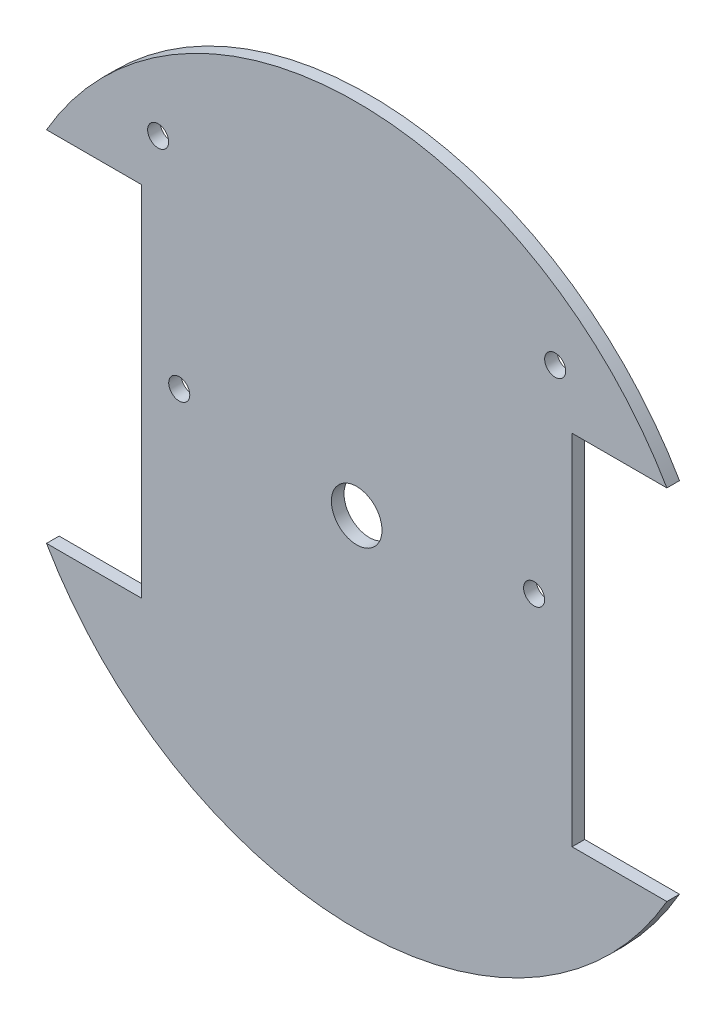
SolidWorks part; units mm, degrees
ref_plane "Plan de face" through (0, 0, 0) normal (0, 0, 1) x (1, 0, 0)
ref_plane "Plan de dessus" through (0, 0, 0) normal (0, 1, 0) x (1, 0, 0)
ref_plane "Plan de droite" through (0, 0, 0) normal (1, 0, 0) x (0, 0, -1)
sketch "Esquisse1" plane through (0, 0, 0) normal (0, 0, 1) x (1, 0, 0)
  circle A0 centre (-147.9597, 62.5489) radius 85
  dimension "D1" = 170
extrude "Boss.-Extru.1" add sketch "Esquisse1" along normal blind 3
sketch "Esquisse2" plane through (0, 0, 0) normal (0, 0, 1) x (1, 0, 0)
  line L0 (-147.9597, 147.5489) -> (-147.9597, -22.4511) construction
  line L1 (-231.5719, 105.0489) -> (-199.0719, 105.0489)
  line L2 (-231.5719, 105.0489) -> (-231.5719, 20.0489)
  line L3 (-231.5719, 20.0489) -> (-199.0719, 20.0489)
  line L4 (-199.0719, 105.0489) -> (-199.0719, 20.0489)
  line L5 (-62.9597, 62.5489) -> (-232.9597, 62.5489) construction
  line L6 (-231.5719, 62.5489) -> (-201.5719, 62.5489) construction
  line L7 (-64.3476, 20.0489) -> (-96.8476, 20.0489)
  line L8 (-64.3476, 105.0489) -> (-64.3476, 20.0489)
  line L9 (-64.3476, 105.0489) -> (-96.8476, 105.0489)
  line L10 (-96.8476, 105.0489) -> (-96.8476, 20.0489)
  circle A0 centre (-147.9597, 62.5489) radius 85 construction
  arc A1 (-221.5719, 105.0489) -> (-221.5719, 20.0489) centre (-147.9597, 62.5489) ccw
  arc A2 (-74.3476, 105.0489) -> (-74.3476, 20.0489) centre (-147.9597, 62.5489) ccw
  dimension "D1" = 85
  dimension "D2" = 32.5
extrude "Enlèv. mat.-Extru.6" cut sketch "Esquisse2" against normal blind 3 from surface at 3 contours L1 A1 L2 L3 L4 | L9 L10 L7 L8 starting at face at (-62.9597, 62.5489, 3)
delete or keep bodies "Corps-Supprimer/Garder 1" type delete bodies bodies 104 103
sketch "Esquisse53" plane through (0, 0, 0) normal (0, 0, -1) x (-1, 0, 0)
  line L0 (199.0719, 62.5489) -> (96.8476, 62.5489) construction
  line L1 (199.0719, 20.0489) -> (199.0719, 105.0489) construction
  line L2 (96.8476, 20.0489) -> (96.8476, 105.0489) construction
  line L3 (105.8476, 62.5489) -> (105.8476, 22.5155) construction
  line L4 (105.8476, 22.5155) -> (190.0719, 22.5155) construction
  line L5 (190.0719, 22.5155) -> (190.0719, 62.5489) construction
  circle A0 centre (190.0719, 67.5489) radius 2.5
  circle A1 centre (105.8476, 67.5489) radius 2.5
  dimension "D3" = 0
  dimension "D1" = 9
  dimension "D2" = 9
  dimension "D4" = 5
  dimension "D5" = 5
extrude "Enlèv. mat.-Extru.21" cut sketch "Esquisse53" against normal blind 10
sketch "Esquisse54" plane through (0, 0, 0) normal (0, 0, -1) x (-1, 0, 0)
  line L0 (195.0719, 133.2981) -> (195.0719, 14.2319) construction
  line L1 (199.0719, 20.0489) -> (199.0719, 105.0489) construction
  line L2 (213.1882, 117.0489) -> (82.7313, 117.0489) construction
  line L3 (199.0719, 105.0489) -> (221.5719, 105.0489) construction
  line L4 (147.9597, 147.5489) -> (147.9597, -22.4511) construction
  arc A0 (221.5719, 105.0489) -> (74.3476, 105.0489) centre (147.9597, 62.5489) ccw construction
  circle A1 centre (195.0719, 117.0489) radius 2.5
  arc A2 (74.3476, 20.0489) -> (221.5719, 20.0489) centre (147.9597, 62.5489) ccw construction
  circle A3 centre (100.8476, 117.0489) radius 2.5
  dimension "D1" = 4
  dimension "D2" = 12
extrude "Enlèv. mat.-Extru.22" cut sketch "Esquisse54" against normal blind 10
sketch "Esquisse55" plane through (0, 0, 0) normal (0, 0, -1) x (-1, 0, 0)
  line L0 (147.9597, 147.5489) -> (147.9597, -22.4511) construction
  line L1 (147.9597, -22.4511) -> (199.0719, 62.5489) construction
  line L2 (199.0719, 20.0489) -> (199.0719, 105.0489) construction
  line L3 (199.0719, 62.5489) -> (96.8476, 62.5489) construction
  line L4 (96.8476, 20.0489) -> (96.8476, 105.0489) construction
  arc A0 (221.5719, 105.0489) -> (74.3476, 105.0489) centre (147.9597, 62.5489) ccw construction
  arc A1 (74.3476, 20.0489) -> (221.5719, 20.0489) centre (147.9597, 62.5489) ccw construction
  circle A2 centre (147.9597, 62.5489) radius 6
extrude "Enlèv. mat.-Extru.23" cut sketch "Esquisse55" against normal blind 10
